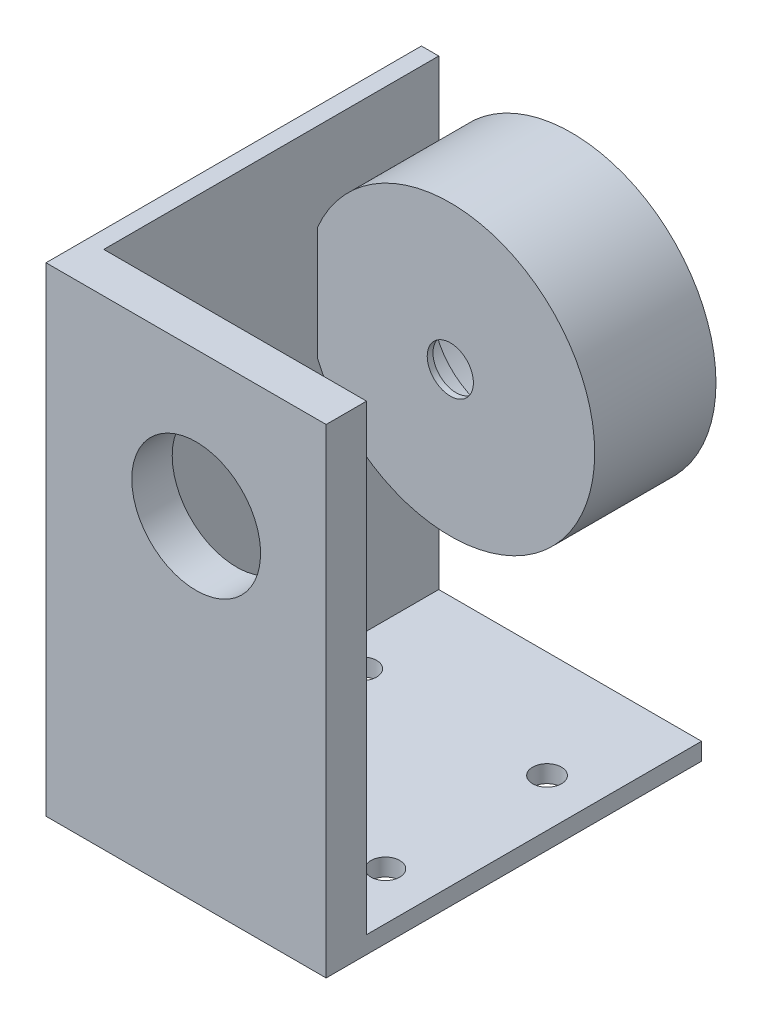
SolidWorks part; units mm, degrees
ref_plane "Front Plane" through (0, 0, 0) normal (0, 0, 1) x (1, 0, 0)
ref_plane "Top Plane" through (0, 0, 0) normal (0, 1, 0) x (1, 0, 0)
ref_plane "Right Plane" through (0, 0, 0) normal (1, 0, 0) x (0, 0, -1)
sketch "Sketch2" plane through (0, 0, 0) normal (0, 1, 0) x (1, 0, 0)
  line L0 (-55, 0) -> (55, 0) construction
  line L1 (-24.25, -32.5) -> (24.25, -32.5)
  line L2 (-24.25, -32.5) -> (-24.25, 32.5)
  line L3 (-24.25, 32.5) -> (24.25, 32.5)
  line L4 (24.25, -32.5) -> (24.25, 32.5)
  line L5 (-24.25, -32.5) -> (24.25, 32.5) construction
  line L6 (-24.25, 32.5) -> (24.25, -32.5) construction
  line L7 (0, -55) -> (0, 55) construction
  circle A0 centre (-16, 14) radius 2.5
  circle A1 centre (16, 14) radius 2.5
  circle A2 centre (16, -14) radius 2.5
  circle A3 centre (-16, -14) radius 2.5
  point P0 (0, 0)
  dimension "D5" = 5
  dimension "D1" = 48.5
  dimension "D2" = 65
  dimension "D3" = 14
  dimension "D4" = 16
extrude "Boss-Extrude1" add sketch "Sketch2" along normal blind 3
sketch "Sketch3" plane through (0, 3, 0) normal (0, 1, 0) x (1, 0, 0)
  line L0 (-24.25, 32.5) -> (-24.25, -32.5)
  line L1 (-24.25, -32.5) -> (24.25, -32.5)
  line L4 (24.25, 32.5) -> (-24.25, 32.5) construction
  line L6 (24.25, -25.5) -> (-21.25, -25.5)
  line L7 (-21.25, -25.5) -> (-21.25, 32.5)
  line L8 (-21.25, 32.5) -> (-24.25, 32.5)
  line L9 (24.25, -32.5) -> (24.25, 32.5) construction
  line L10 (24.25, -25.5) -> (24.25, -32.5)
  dimension "D2" = 7
  dimension "D3" = 3
extrude "Boss-Extrude2" add sketch "Sketch3" along normal blind 80
sketch "Sketch6" plane through (0, 0, -32.5) normal (0, 0, -1) x (-1, 0, 0)
  line L0 (-24.25, 83) -> (21.25, 83) construction
  line L1 (21.25, 67.798) -> (21.25, 48.202)
  line L2 (21.25, 83) -> (21.25, 3) construction
  arc A2 (21.25, 67.798) -> (21.25, 48.202) centre (-1.75, 58) ccw
  circle A3 centre (-1.75, 58) radius 22.5
  dimension "D1" = 25
  dimension "D2" = 45
  dimension "D3" = 23
extrude "Boss-Extrude3" add sketch "Sketch6" against normal blind 13
sketch "Sketch10" plane through (0, 0, -19.5) normal (0, 0, 1) x (1, 0, 0)
  line L1 (-21.25, 67.798) -> (-21.25, 48.202)
  arc A1 (-21.25, 67.798) -> (-21.25, 48.202) centre (1.75, 58) cw
  dimension "D1" = 25
extrude "Boss-Extrude4" add sketch "Sketch10" along normal blind 8
sketch "Sketch12" plane through (0, 0, -19.5) normal (0, 0, -1) x (-1, 0, 0)
  circle A0 centre (-1.75, 58) radius 11.1
  dimension "D1" = 22.2
extrude "Cut-Extrude1" cut sketch "Sketch12" against normal blind 7
sketch "Sketch13" plane through (0, 0, -12.5) normal (0, 0, -1) x (-1, 0, 0)
  circle A0 centre (-1.75, 58) radius 4
  dimension "D1" = 8
extrude "Cut-Extrude2" cut sketch "Sketch13" against normal blind 78
sketch "Sketch14" plane through (0, 0, 25.5) normal (0, 0, -1) x (-1, 0, 0)
  circle A4 centre (-1.75, 58) radius 11.15
  dimension "D2" = 22.3
extrude "Cut-Extrude3" cut sketch "Sketch14" against normal blind 10
